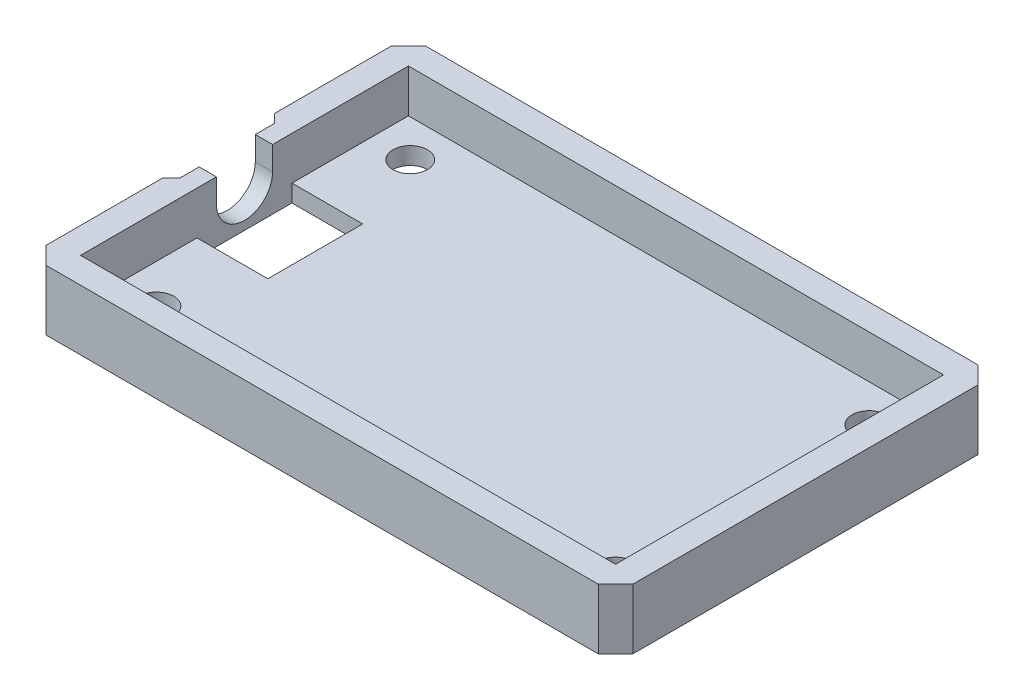
SolidWorks part; units mm, degrees
ref_plane "Front Plane" through (0, 0, 0) normal (0, 0, 1) x (1, 0, 0)
ref_plane "Top Plane" through (0, 0, 0) normal (0, 1, 0) x (1, 0, 0)
ref_plane "Right Plane" through (0, 0, 0) normal (1, 0, 0) x (0, 0, -1)
sketch "Sketch1" plane through (0, 0, 0) normal (0, 1, 0) x (1, 0, 0)
  line L0 (-33.2841, -14.3182) -> (-33.2841, -27.8182)
  line L1 (-33.2841, 10.1818) -> (28.7159, 10.1818)
  line L2 (-33.2841, 10.1818) -> (-33.2841, -3.3182)
  line L3 (-33.2841, -27.8182) -> (28.7159, -27.8182)
  line L4 (28.7159, 10.1818) -> (28.7159, -27.8182)
  line L5 (-36.2841, 13.1818) -> (31.7159, 13.1818)
  line L6 (-36.2841, 13.1818) -> (-36.2841, -3.3182)
  line L7 (-36.2841, -30.8182) -> (31.7159, -30.8182)
  line L8 (31.7159, 13.1818) -> (31.7159, -30.8182)
  line L9 (-36.2841, -3.3182) -> (-33.2841, -3.3182)
  line L11 (-36.2841, -14.3182) -> (-33.2841, -14.3182)
  line L13 (-36.2841, -14.3182) -> (-36.2841, -30.8182)
  dimension "D1" = 62
  dimension "D2" = 38
  dimension "D3" = 3
  dimension "D4" = 3
  dimension "D5" = 3
  dimension "D6" = 3
extrude "Boss-Extrude1" add sketch "Sketch1" along normal blind 5
sketch "Sketch2" plane through (0, 0, 0) normal (0, -1, 0) x (1, 0, 0)
  line L1 (-36.2841, -13.1818) -> (31.7159, -13.1818)
  line L2 (-36.2841, -13.1818) -> (-36.2841, 30.8182)
  line L3 (-36.2841, 30.8182) -> (31.7159, 30.8182)
  line L4 (31.7159, -13.1818) -> (31.7159, 30.8182)
extrude "Boss-Extrude2" add sketch "Sketch2" along normal blind 2
sketch "Sketch3" plane through (-36.2841, 0, 0) normal (-1, 0, 0) x (0, 0, 1)
  line L0 (30.8182, -2) -> (-13.1818, -2) construction
  line L1 (3.3182, 0) -> (14.3182, 0)
  line L2 (3.3182, 0) -> (3.3182, -2)
  line L3 (3.3182, -2) -> (14.3182, -2)
  line L4 (14.3182, 0) -> (14.3182, -2)
extrude "Cut-Extrude1" cut sketch "Sketch3" against normal blind 11.2
chamfer "Chamfer1" distance 1 angle 45 2 edges at (-36.2841, 1.5, 14.3182) (-36.2841, 1.5, 3.3182)
sketch "Sketch4" plane through (0, 0, 0) normal (0, 1, 0) x (1, 0, 0)
  line L0 (-33.2841, 10.1818) -> (28.7159, 10.1818) construction
  line L1 (28.7159, 10.1818) -> (28.7159, -27.8182) construction
  line L2 (28.7159, -27.8182) -> (-33.2841, -27.8182) construction
  line L3 (-33.2841, -27.8182) -> (-33.2841, -14.3182) construction
  line L4 (-33.2841, -3.3182) -> (-33.2841, 10.1818) construction
  circle A0 centre (24.4159, 5.8818) radius 2
  circle A1 centre (24.4159, -23.5182) radius 2
  circle A2 centre (-28.7841, -23.5182) radius 2
  circle A3 centre (-28.7841, 5.8818) radius 2
  dimension "D1" = 4
  dimension "D2" = 4.3
  dimension "D3" = 4.3
  dimension "D4" = 4
  dimension "D5" = 4.3
  dimension "D6" = 4.5
  dimension "D7" = 4
  dimension "D8" = 4.3
  dimension "D9" = 4
  dimension "D10" = 4.3
  dimension "D11" = 4.5
  dimension "D16" = 4.3
extrude "Cut-Extrude2" cut sketch "Sketch4" against normal blind 10
sketch "Sketch6" plane through (0, 0, 14.3182) normal (0, 0, -1) x (-1, 0, 0)
  line L1 (33.2841, 5) -> (35.2841, 5)
  line L2 (33.2841, 5) -> (33.2841, -2)
  line L3 (33.2841, -2) -> (35.2841, -2)
  line L4 (35.2841, 5) -> (35.2841, -2)
extrude "Boss-Extrude3" add sketch "Sketch6" along normal blind 20
sketch "Sketch7" plane through (-35.2841, 0, 0) normal (-1, 0, 0) x (0, 0, 1)
  line L0 (3.3182, -2) -> (14.3182, -2) construction
  line L1 (5.5682, 2.25) -> (5.5682, 5)
  line L2 (3.3182, 5) -> (14.3182, 5) construction
  line L3 (5.5682, 5) -> (12.0682, 5)
  line L4 (12.0682, 5) -> (12.0682, 2.25)
  arc A0 (5.5682, 2.25) -> (12.0682, 2.25) centre (8.8182, 2.25) ccw
  dimension "D1" = 6.5
  dimension "D2" = 4.25
extrude "Cut-Extrude3" cut sketch "Sketch7" against normal blind 5
chamfer "Chamfer2" distance 2 angle 45 4 edges at (-36.2841, 1.5, -13.1818) (31.7159, 1.5, -13.1818) (31.7159, 1.5, 30.8182) (-36.2841, 1.5, 30.8182)
